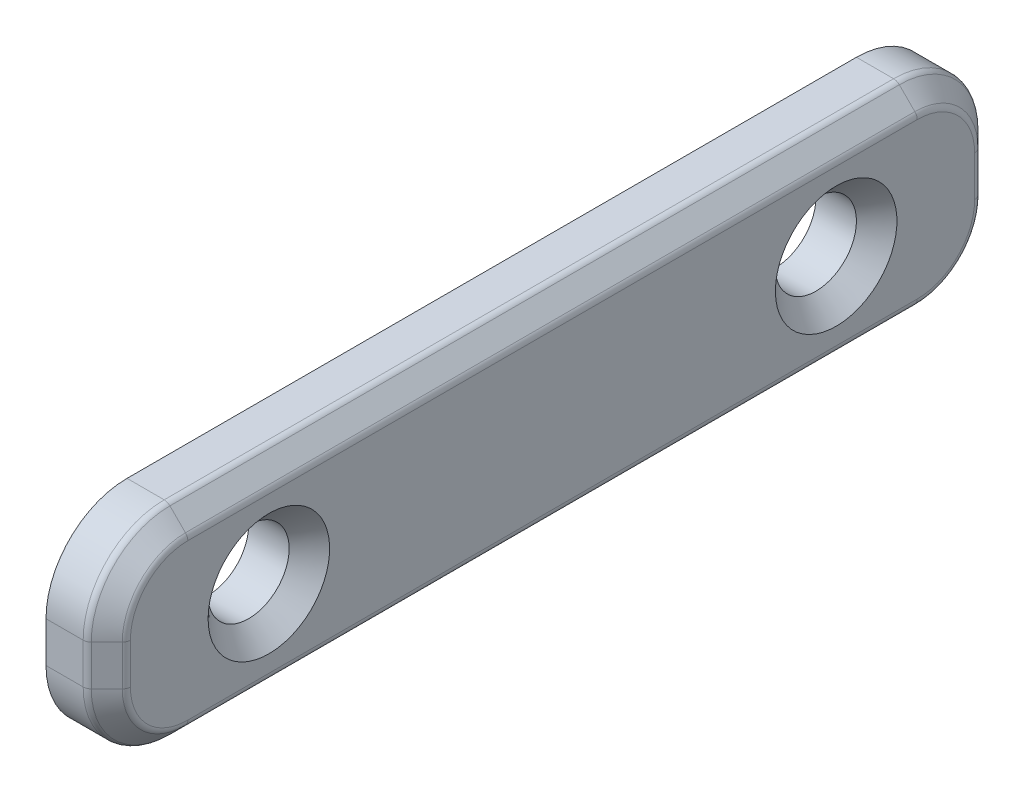
SolidWorks part; units mm, degrees
material "moto_white"
ref_plane "Front Plane" through (0, 0, 0) normal (0, 0, 1) x (1, 0, 0)
ref_plane "Top Plane" through (0, 0, 0) normal (0, 1, 0) x (1, 0, 0)
ref_plane "Right Plane" through (0, 0, 0) normal (1, 0, 0) x (0, 0, -1)
sketch "Sketch1" plane through (0, 0, 0) normal (1, 0, 0) x (0, 0, -1)
  line L1 (-18, -5) -> (18, -5)
  line L2 (-22, -1) -> (-22, 1)
  line L3 (-18, 5) -> (18, 5)
  line L4 (22, -1) -> (22, 1)
  line L5 (-22, -5) -> (22, 5) construction
  line L6 (-22, 5) -> (22, -5) construction
  arc A0 (18, 5) -> (22, 1) centre (18, 1) cw
  arc A1 (18, -5) -> (22, -1) centre (18, -1) ccw
  arc A2 (-18, -5) -> (-22, -1) centre (-18, -1) cw
  arc A3 (-18, 5) -> (-22, 1) centre (-18, 1) ccw
  point P0 (0, 0)
  dimension "D3" = 4
  dimension "D1" = 44
  dimension "D2" = 10
extrude "Boss-Extrude1" add sketch "Sketch1" along normal blind 3
chamfer "Chamfer1" distance 1 angle 45 8 edges at (3, 0, -22) (3, -3.8284, -20.8284) (3, -5, 0) (3, -3.8284, 20.8284) (3, 0, 22) (3, 3.8284, 20.8284) (3, 5, 0) (3, 3.8284, -20.8284)
fillet "Fillet1" radius 0.4 16 edges at (2, 3.8284, 20.8284) (2, 0, 22) (2, -3.8284, 20.8284) (2, -5, 0) (2, -3.8284, -20.8284) (2, 0, -22) (2, 3.8284, -20.8284) (3, 3.1213, -20.1213) (3, 0, -21) (3, -3.1213, -20.1213) (3, -4, 0) (3, -3.1213, 20.1213) (3, 0, 21) (3, 3.1213, 20.1213) (2, 5, 0) (3, 4, 0)
sketch "Sketch2" plane through (3, 0, 0) normal (1, 0, 0) x (0, 0, -1)
  line L0 (0, 3.8343) -> (0, -3.8343)
  line L1 (18, 3.8343) -> (-18, 3.8343) construction
  line L2 (-18, -3.8343) -> (18, -3.8343) construction
  circle A0 centre (-14, 0) radius 2
  circle A1 centre (14, 0) radius 2
  dimension "D1" = 4
  dimension "D2" = 14
extrude "Cut-Extrude1" cut sketch "Sketch2" against normal blind 3 contours A0 | A1
chamfer "Chamfer2" distance 1 angle 45 2 edges at (3, 0, 12) (3, 0, -16)
